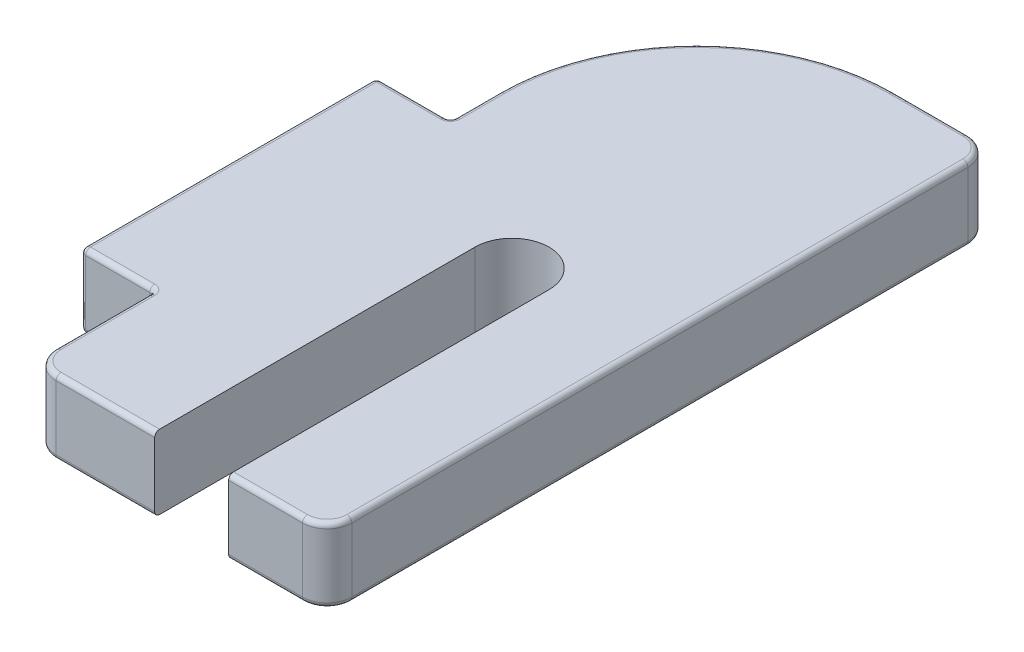
SolidWorks part; units mm, degrees
ref_plane "Front Plane" through (0, 0, 0) normal (0, 0, 1) x (1, 0, 0)
ref_plane "Top Plane" through (0, 0, 0) normal (0, 1, 0) x (1, 0, 0)
ref_plane "Right Plane" through (0, 0, 0) normal (1, 0, 0) x (0, 0, -1)
sketch "Sketch1" plane through (0, 0, 0) normal (0, 1, 0) x (1, 0, 0)
  line L0 (-1.5, 0) -> (-1.5, -13)
  line L1 (1.5, 0) -> (1.5, -13)
  line L2 (1.5, -13) -> (4.5, -13)
  line L3 (5.5, -12) -> (5.5, 13)
  line L4 (4.5, 14) -> (1.5, 14)
  line L5 (-6.5, 6) -> (-6.5, 4)
  line L6 (-6.5, 4) -> (-9.5, 4)
  line L7 (-9.5, 4) -> (-9.5, -8)
  line L8 (-9.5, -8) -> (-6.5, -8)
  line L9 (-6.5, -8) -> (-6.5, -12)
  line L10 (-5.5, -13) -> (-1.5, -13)
  arc A0 (1.5, 0) -> (-1.5, 0) centre (0, 0) ccw
  arc A1 (1.5, 14) -> (-6.5, 6) centre (1.5, 6) ccw
  arc A2 (-6.5, -12) -> (-5.5, -13) centre (-5.5, -12) ccw
  arc A3 (4.5, -13) -> (5.5, -12) centre (4.5, -12) ccw
  arc A4 (5.5, 13) -> (4.5, 14) centre (4.5, 13) ccw
  point P18 (-6.5, -13)
  point P21 (5.5, -13)
  point P24 (5.5, 14)
  dimension "D1" = 1.5
  dimension "D9" = 8
  dimension "D10" = 1
  dimension "D2" = 4
  dimension "D3" = 5
  dimension "D4" = 27
  dimension "D5" = 13
  dimension "D6" = 12
  dimension "D7" = 5
  dimension "D8" = 3
extrude "Boss-Extrude1" add sketch "Sketch1" along normal blind 3
fillet "Fillet1" radius 0.2 30 edges at (-8, 0, 8) (-8, 3, 8) (-8, 0, -4) (-8, 3, -4) (-6.5, 0, 10) (-6.2071, 0, 12.7071) (-6.5, 3, 10) (-6.2071, 3, 12.7071) (-6.5, 0, -5) (-4.1569, 0, -11.6569) (3, 0, -14) (5.2071, 0, -13.7071) (5.5, 0, -0.5) (5.2071, 0, 12.7071) (3, 3, 13) (-6.5, 3, -5) (-4.1569, 3, -11.6569) (3, 3, -14) (5.2071, 3, -13.7071) (5.5, 3, -0.5) (-9.5, 1.5, -4) (-9.5, 3, 2) (-9.5, 1.5, 8) (-9.5, 0, 2) (-6.5, 1.5, -4) (-6.5, 1.5, 8) (-3.5, 0, 13) (-3.5, 3, 13) (3, 0, 13) (5.2071, 3, 12.7071)
ref_plane "Plane1" through (0, 0, 0) normal (0, 0, 1) x (0, -1, 0)
